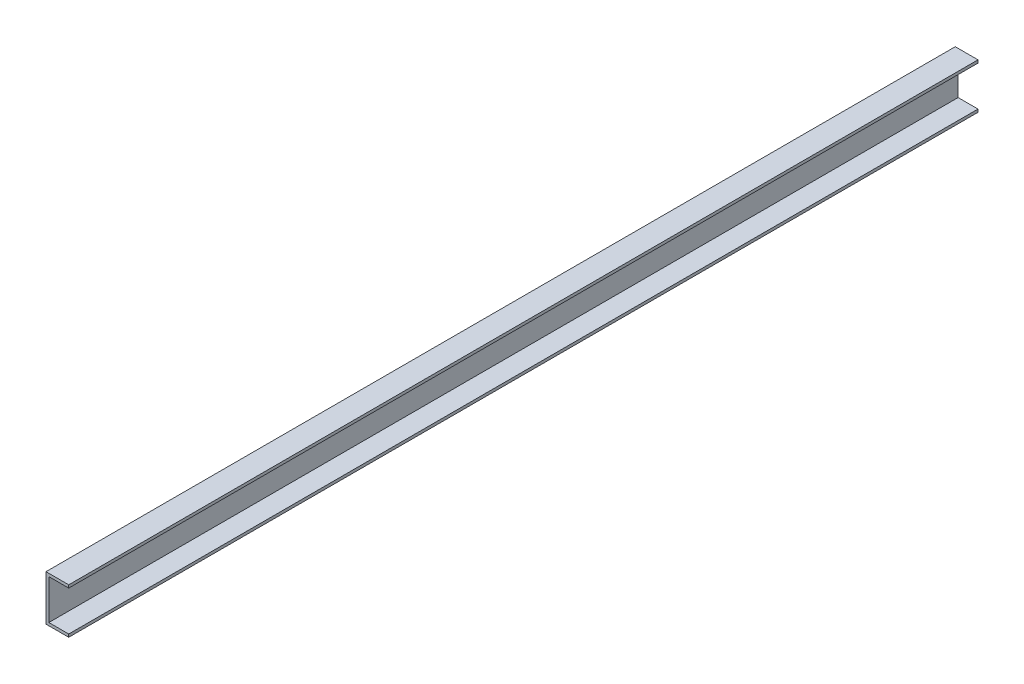
SolidWorks part; units mm, degrees
ref_plane "Front" through (0, 0, 0) normal (0, 0, 1) x (1, 0, 0)
ref_plane "Top" through (0, 0, 0) normal (0, 1, 0) x (1, 0, 0)
ref_plane "Right" through (0, 0, 0) normal (1, 0, 0) x (0, 0, -1)
sketch "Sketch1" plane through (0, 0, 0) normal (0, 0, 1) x (1, 0, 0)
  line L0 (0, 0) -> (0, 50.8)
  line L1 (25.4, 50.8) -> (25.4, 47.625)
  line L2 (0, 0) -> (25.4, 0)
  line L3 (25.4, 3.175) -> (3.175, 3.175)
  line L4 (3.175, 47.625) -> (3.175, 3.175)
  line L5 (25.4, 47.625) -> (3.175, 47.625)
  line L6 (0, 50.8) -> (25.4, 50.8)
  line L7 (25.4, 0) -> (25.4, 3.175)
extrude "Extrude1" add sketch "Sketch1" along normal blind 1016
